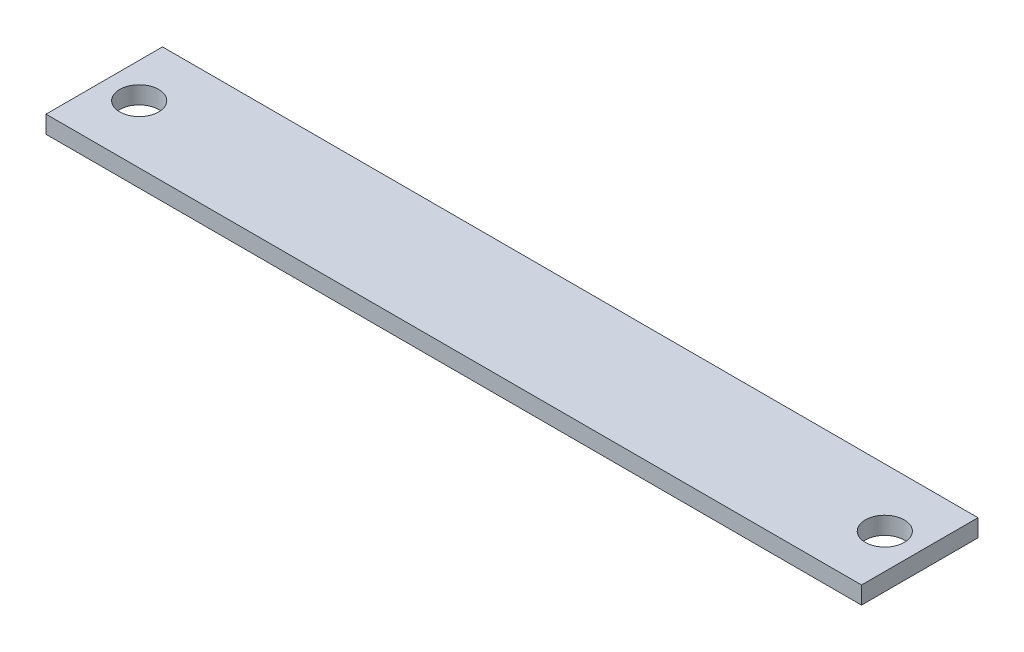
SolidWorks part; units mm, degrees
ref_plane "Front Plane" through (0, 0, 0) normal (0, 0, 1) x (1, 0, 0)
ref_plane "Top Plane" through (0, 0, 0) normal (0, 1, 0) x (1, 0, 0)
ref_plane "Right Plane" through (0, 0, 0) normal (1, 0, 0) x (0, 0, -1)
sketch "Sketch1" plane through (0, 0, 0) normal (0, 1, 0) x (1, 0, 0)
  line L0 (-104.5022, 11.039) -> (35.4978, 11.039) construction
  line L1 (-104.5022, 21.039) -> (35.4978, 21.039)
  line L2 (-104.5022, 21.039) -> (-104.5022, 1.039)
  line L3 (-104.5022, 1.039) -> (35.4978, 1.039)
  line L4 (35.4978, 21.039) -> (35.4978, 1.039)
  circle A0 centre (-98.5022, 11.039) radius 3.35
  circle A1 centre (29.4978, 11.039) radius 3.35
  dimension "D3" = 6.7
  dimension "D4" = 6.7
  dimension "D1" = 20
  dimension "D2" = 140
  dimension "D5" = 128
  dimension "D6" = 6
extrude "Boss-Extrude1" add sketch "Sketch1" along normal blind 3
